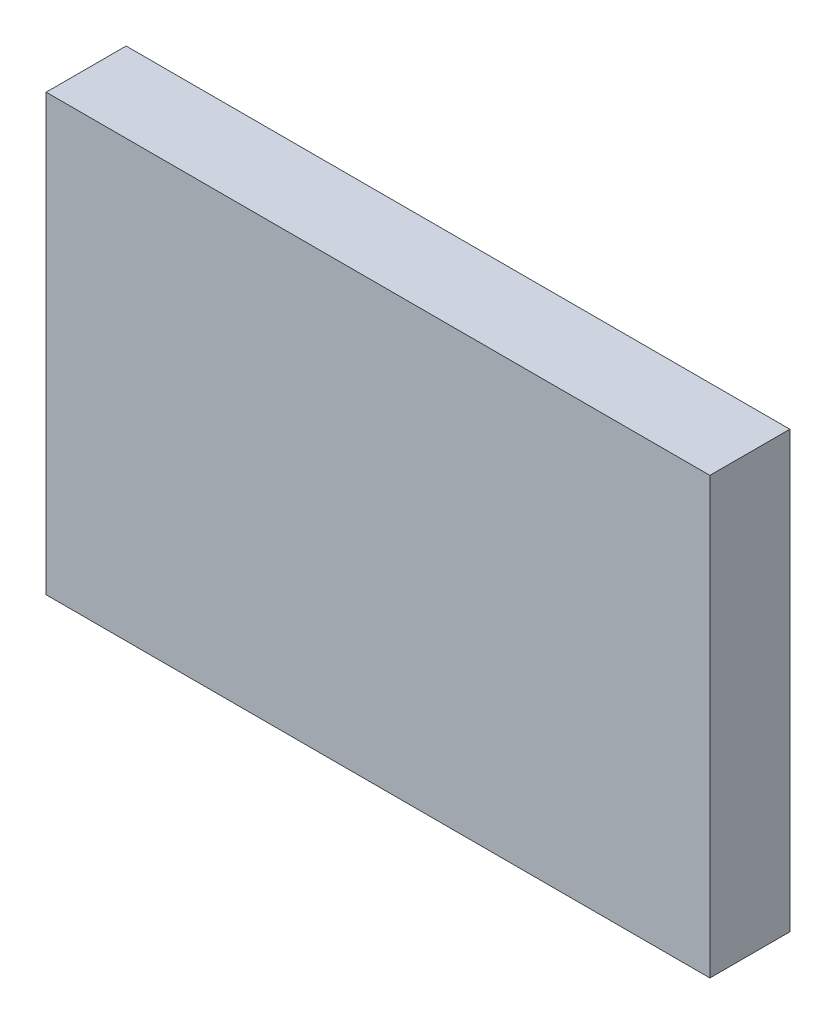
SolidWorks part; units mm, degrees
ref_plane "Plan de face" through (0, 0, 0) normal (0, 0, 1) x (1, 0, 0)
ref_plane "Plan de dessus" through (0, 0, 0) normal (0, 1, 0) x (1, 0, 0)
ref_plane "Plan de droite" through (0, 0, 0) normal (1, 0, 0) x (0, 0, -1)
sketch "Esquisse1" plane through (0, 0, 0) normal (0, 0, 1) x (1, 0, 0)
  line L1 (-39.3659, -22.7824) -> (12.9341, -22.7824)
  line L2 (-39.3659, -22.7824) -> (-39.3659, 11.5176)
  line L3 (-39.3659, 11.5176) -> (12.9341, 11.5176)
  line L4 (12.9341, -22.7824) -> (12.9341, 11.5176)
  dimension "D1" = 34.3
  dimension "D2" = 52.3
extrude "Boss.-Extru.1" add sketch "Esquisse1" along normal blind 6.3
